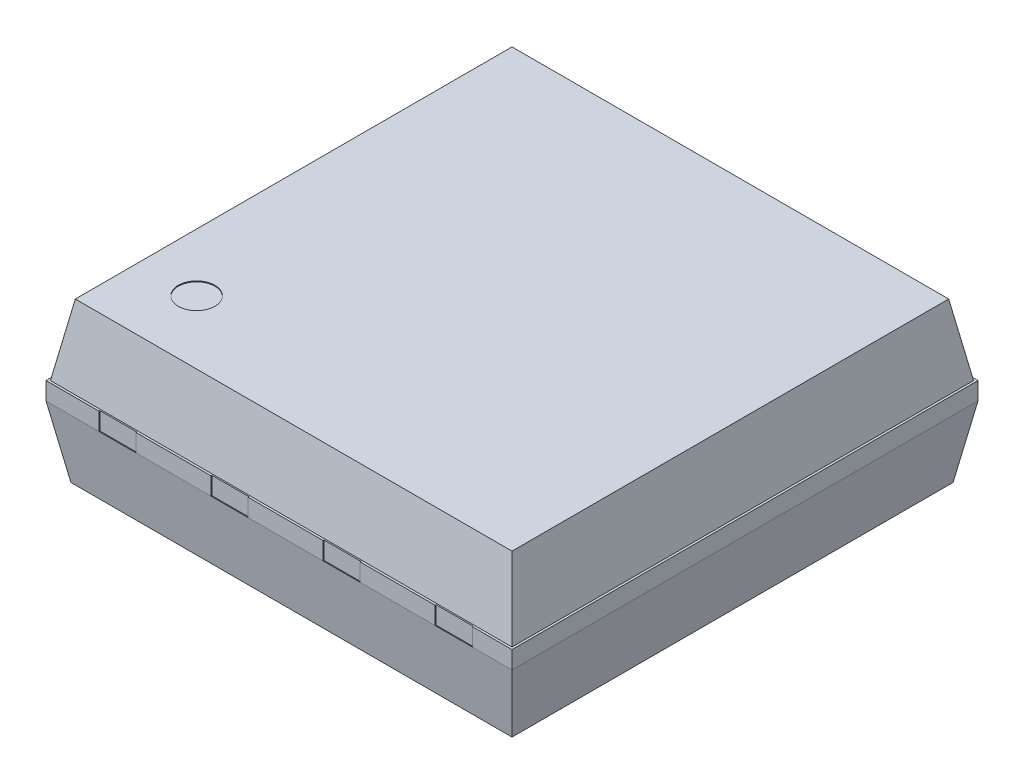
SolidWorks part; units mm, degrees
ref_plane "Front Plane" through (0, 0, 0) normal (0, 0, 1) x (1, 0, 0)
ref_plane "Top Plane" through (0, 0, 0) normal (0, 1, 0) x (1, 0, 0)
ref_plane "Right Plane" through (0, 0, 0) normal (1, 0, 0) x (0, 0, -1)
sketch "Sketch3" plane through (0, 0, 0) normal (0, 1, 0) x (1, 0, 0)
  line L1 (-2.615, 2.615) -> (2.615, 2.615)
  line L2 (-2.615, 2.615) -> (-2.615, -2.615)
  line L3 (-2.615, -2.615) -> (2.615, -2.615)
  line L4 (2.615, 2.615) -> (2.615, -2.615)
  line L5 (-2.615, 2.615) -> (2.615, -2.615) construction
  line L6 (-2.615, -2.615) -> (2.615, 2.615) construction
  point P0 (0, 0)
  dimension "D1" = 5.23
  dimension "D2" = 5.23
extrude "Boss-Extrude1" add sketch "Sketch3" along normal blind 0.8 draft 10
sketch "Sketch4" plane through (0, 0, 0) normal (0, -1, 0) x (1, 0, 0)
  line L1 (-2.64, 2.64) -> (2.64, 2.64)
  line L2 (-2.64, 2.64) -> (-2.64, -2.64)
  line L3 (-2.64, -2.64) -> (2.64, -2.64)
  line L4 (2.64, 2.64) -> (2.64, -2.64)
  line L5 (-2.64, 2.64) -> (2.64, -2.64) construction
  line L6 (-2.64, -2.64) -> (2.64, 2.64) construction
  point P0 (0, 0)
  dimension "D1" = 5.28
  dimension "D2" = 5.28
extrude "Boss-Extrude2" add sketch "Sketch4" along normal blind 0.2 separate body
sketch "Sketch5" plane through (0, -0.2, 0) normal (0, -1, 0) x (1, 0, 0)
  line L4 (2.64, -2.64) -> (2.64, 2.64)
  line L5 (2.64, 2.64) -> (-2.64, 2.64)
  line L6 (-2.64, 2.64) -> (-2.64, -2.64)
  line L7 (-2.64, -2.64) -> (2.64, -2.64)
  line L8 (2.64, -2.64) -> (2.64, 2.64)
  line L9 (2.64, 2.64) -> (-2.64, 2.64)
  line L10 (-2.64, 2.64) -> (-2.64, -2.64)
  line L11 (-2.64, -2.64) -> (2.64, -2.64)
  dimension "D1" = 0
extrude "Boss-Extrude3" add sketch "Sketch5" along normal blind 0.8 draft 10 separate body
sketch "Sketch6" plane through (0, 0.8, 0) normal (0, 1, 0) x (1, 0, 0)
  circle A0 centre (-1.8186, -1.755) radius 0.207
extrude "Cut-Extrude1" cut sketch "Sketch6" against normal blind 0.01
sketch "Sketch8" plane through (0, 0, 2.64) normal (0, 0, 1) x (1, 0, 0)
  line L0 (-2.615, 0) -> (2.615, 0) construction
  line L1 (-2.04, 0) -> (-1.62, 0)
  line L2 (-2.04, 0) -> (-2.04, -0.2)
  line L3 (-2.04, -0.2) -> (-1.62, -0.2)
  line L4 (-1.62, 0) -> (-1.62, -0.2)
  line L5 (2.64, -0.2) -> (-2.64, -0.2) construction
  line L6 (-0.77, 0) -> (-0.35, 0)
  line L7 (-0.35, 0) -> (-0.35, -0.2)
  line L8 (-0.77, -0.2) -> (-0.35, -0.2)
  line L9 (-0.77, 0) -> (-0.77, -0.2)
  line L10 (0.5, 0) -> (0.92, 0)
  line L11 (0.92, 0) -> (0.92, -0.2)
  line L12 (0.5, -0.2) -> (0.92, -0.2)
  line L13 (0.5, 0) -> (0.5, -0.2)
  line L14 (1.77, 0) -> (2.19, 0)
  line L15 (2.19, 0) -> (2.19, -0.2)
  line L16 (1.77, -0.2) -> (2.19, -0.2)
  line L17 (1.77, 0) -> (1.77, -0.2)
  line L18 (-2.64, -0.2) -> (-2.64, 0) construction
  point P22 (-2.64, -0.1)
  dimension "D1" = 0.42
  dimension "D3" = 0.6
  dimension "D2" = 4
extrude "Cut-Extrude2" cut sketch "Sketch8" against normal blind 0.01
mirror "Mirror1" about plane through (0, 0, 0) normal (0, 0, 1) of "Cut-Extrude2"
